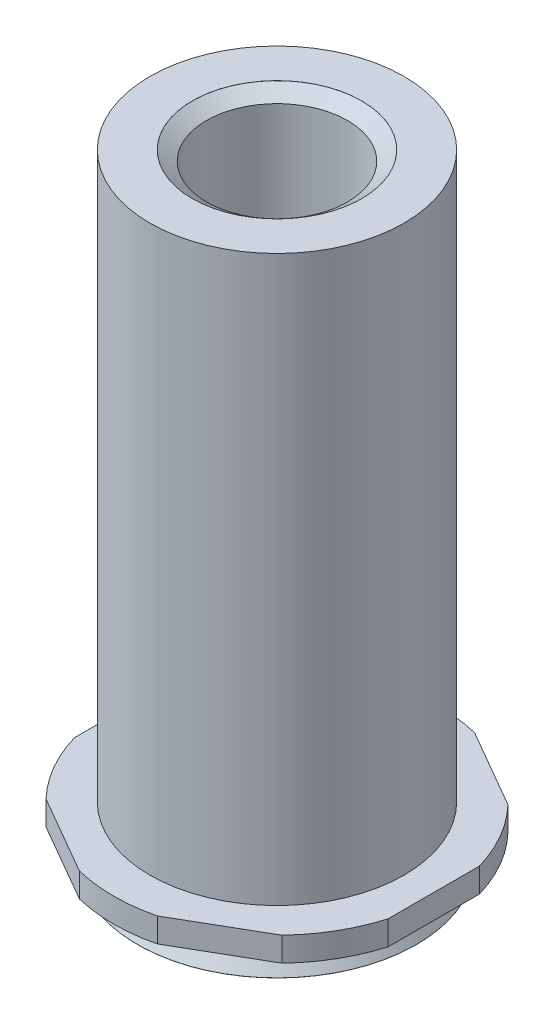
SolidWorks part; units mm, degrees
revolve "Body" add sketch "BodySke"
sketch "BodySke" plane through (0, 0, 0) normal (0, 0, 1) x (1, 0, 0)
  line L0 (4.5006, 0) -> (5.7851, 0)
  line L1 (5.7851, 0) -> (5.7851, 0.8595)
  line L2 (5.7851, 0.8595) -> (4.5, 0.8595)
  line L3 (2.5, 20.8595) -> (2.5, 11.2595)
  line L4 (0, -1.0505) -> (4.94, -1.0505)
  line L5 (4.94, -1.0505) -> (4.94, -1.0475)
  line L6 (4.94, -1.0475) -> (4.5006, -0.2865)
  line L7 (1.016, 19.8595) -> (3.6522, 19.8595) construction
  line L8 (4.5, 20.8595) -> (2.5, 20.8595)
  line L9 (0, 0) -> (0, 15.24) construction
  line L10 (4.5006, -0.2865) -> (4.5006, 0)
  line L11 (4.5, 20.8595) -> (4.5, 0.8595)
  line L12 (0, 11.2595) -> (2.5, 11.2595)
  line L13 (0, 11.2595) -> (0, -1.0505)
  line L14 (1.016, 11.2595) -> (3.6522, 11.2595) construction
  line L15 (1.016, 11.2595) -> (3.6522, 11.2595) construction
  dimension "E_dia" = 11.5702
  dimension "C_dia" = 9.88
  dimension "A_ht" = 1.0505
  dimension "Thread_min" = 5
  dimension "C_len" = 0.003
  dimension "Clinching_ht" = 0.2865
  dimension "D1" = 60
  dimension "Thickness" = 1.91
  dimension "B_dia" = 9
  dimension "Length" = 20
  dimension "Thread_limit" = 9.6
  dimension "Advance" = 1
  dimension "Thread_depth" = 9.6
  dimension "Drill_depth" = 9.6
cosmetic thread "ThreadCosmetic" [suppressed]
revolve "EndChamfer" cut sketch "EndChamferSke" angle 360 about L0
sketch "EndChamferSke" plane through (0, 0, 0) normal (0, 0, 1) x (1, 0, 0)
  line L0 (0, -2.54) -> (0, 7.62) construction
  line L1 (0, 0) -> (0, 15.24) construction
  line L6 (3, 20.857) -> (2.5, 20.507)
  line L7 (3, 20.857) -> (3, 21.1135)
  line L8 (2.5, 20.507) -> (2.5, 21.1135)
  line L9 (3, 21.1135) -> (2.5, 21.1135)
  line L10 (4.5, 20.8595) -> (-4.5, 20.8595) construction
  dimension "D1" = 0.254
  dimension "Thread_nominal" = 6
  dimension "D2" = 34.99
  dimension "Thread_min" = 5
  dimension "Inset" = 0.0025
revolve "TapDrill" cut sketch "TapDriSke" angle 360 about L0
sketch "TapDriSke" plane through (0, 0, 0) normal (0, 0, 1) x (1, 0, 0)
  line L0 (0, 0) -> (0, 15.24) construction
  line L1 (0, 0) -> (0, 15.24) construction
  line L2 (2.5, 6.2595) -> (2.5, 20.8595)
  line L3 (4.5, 20.8595) -> (-4.5, 20.8595) construction
  line L4 (2.5, 6.2595) -> (0, 5.224)
  line L5 (0, 5.224) -> (0, 20.8595)
  line L6 (0, 20.8595) -> (2.5, 20.8595)
  line L7 (2.5, 11.2595) -> (2.5, 20.8595) construction
  line L8 (0, 5.224) -> (-2.5, 6.2595) construction
  line L9 (-2.5, 20.8595) -> (-2.5, 11.2595) construction
  dimension "D1" = 135
ref_plane "Plane1" through (0, 0, 0) normal (0, 0, 1) x (1, 0, 0)
ref_plane "Plane2" through (0, 0, 0) normal (0, 1, 0) x (1, 0, 0)
ref_plane "Plane3" through (0, 0, 0) normal (1, 0, 0) x (0, 0, -1)
ref_plane "Plane4" through (0, -0.5486, 0) normal (0, 1, 0) x (-1, 0, 0)
sketch "ThdSchSke" plane through (0, 0, 0) normal (0, 0, 1) x (1, 0, 0)
  line L0 (0, -5.08) -> (0, 7.62) construction
  line L1 (0, 0) -> (0, 15.24) construction
  line L2 (0, 20.857) -> (3, 20.857) construction
  line L3 (3, 20.857) -> (-3, 20.857) construction
  line L4 (3, 20.857) -> (2.5, 21.2071)
  line L6 (3, 20.857) -> (2.5, 20.5069)
  line L7 (2.5, 21.2071) -> (2.5, 20.5069)
  dimension "Thread_min" = 5
revolve "ThreadSchematic" [suppressed] cut sketch "ThdSchSke" angle 360 about L0
pattern_linear "ThdSchPat" [suppressed]
sketch "HexDieSke" plane through (0, 0.8595, 0) normal (0, 1, 0) x (-1, 0, 0)
  line L0 (0, 6.4144) -> (5.555, 3.2072)
  line L1 (5.555, 3.2072) -> (5.555, -3.2072)
  line L2 (5.555, -3.2072) -> (0, -6.4144)
  line L3 (0, -6.4144) -> (-5.555, -3.2072)
  line L4 (-5.555, -3.2072) -> (-5.555, 3.2072)
  line L5 (-5.555, 3.2072) -> (0, 6.4144)
  circle A1 centre (0, 0) radius 5.555 construction
  circle A2 centre (0, 0) radius 6.4144 construction
  circle A3 centre (0, 0) radius 6.4443
extrude "HexDie" cut sketch "HexDieSke" against normal blind 0.8595
equation "' \"Length@BodySke\" = 20"
equation "' \"Thickness@BodySke\" = 1.91"
equation "' \"B_dia@BodySke\" = 9"
equation "' \"C_dia@BodySke\" = 9.88"
equation "' \"Width_across_flats@HexDieSke\" = 11.11"
equation "' \"E_dia@BodySke\" = \"Width_across_flats@HexDieSke\" * 1.04 ' varies by type (1.04 or 1.16)"
equation "' \"Thread_depth@BodySke\" = 9.6"
equation "' \"Drill_depth@BodySke\" = 9.6"
equation "' \"Advance@BodySke\" = 1"
equation "' \"Thread_min@BodySke\" = 5"
equation "' \"Thread_nominal@ThreadCosmetic\" = 6"
equation "\"Thread_limit@BodySke\" = ((sgn( \"Length@BodySke\" - \"Thread_depth@BodySke\" )-1)*( \"Length@BodySke\" - \"Thread_depth@BodySke\" ))/-2+ \"Thread_depth@BodySke\""
equation "\"Depth@TapDriSke\" = \"Thread_limit@BodySke\" + \"Advance@BodySke\" * 5"
equation "\"Depth@TapDriSke\" = ((sgn( \"Depth@TapDriSke\" - \"Drill_depth@BodySke\" )+1)*( \"Depth@TapDriSke\" - \"Drill_depth@BodySke\" ))/2 +\"Drill_depth@BodySke\""
equation "\"A_ht@BodySke\" = \"Thickness@BodySke\" * 0.55"
equation "\"Clinching_ht@BodySke\" = \"Thickness@BodySke\" * 0.15"
equation "\"C_len@BodySke\" =  0.003"
equation "\"Depth@HexDie\" = \"Thickness@BodySke\" - \"A_ht@BodySke\""
equation "\"OD@HexDieSke\" =  \"Width_across_flats@HexDieSke\" * 1.16 + 0.001"
equation "\"Thread_nominal@EndChamferSke\" = \"Thread_nominal@ThreadCosmetic\""
equation "\"Thread_min@EndChamferSke\" = \"Thread_min@BodySke\""
equation "\"D2@EndChamferSke\" = \"Vee_angle@ThdSchSke\" / 2 - 0.01"
equation "\"Thread_nominal@ThdSchSke\" = \"Thread_nominal@ThreadCosmetic\""
equation "\"Thread_min@ThdSchSke\" = \"Thread_min@BodySke\""
equation "\"Num_threads@ThdSchPat\" = int(  ( \"Thread_limit@BodySke\" - \"Inset@EndChamferSke\" ) / \"Advance@BodySke\" + 0.999 )  + 1"
equation "\"Advance@ThdSchPat\" = (  \"Thread_limit@BodySke\" - \"Inset@EndChamferSke\" ) /  (\"Num_threads@ThdSchPat\" - 1) 'relax it"
